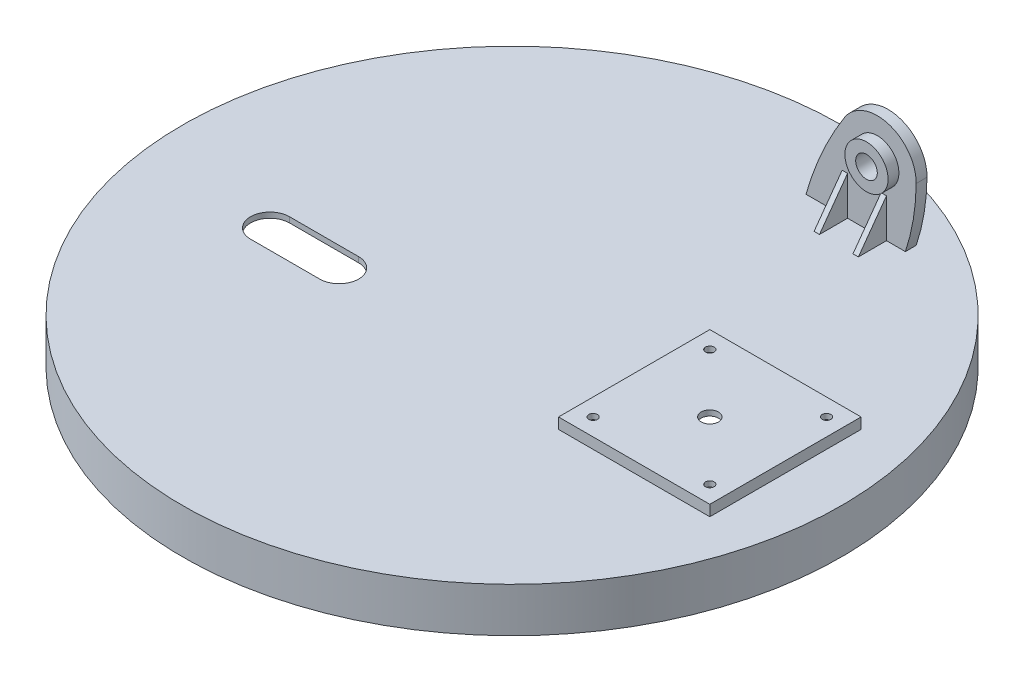
SolidWorks part; units mm, degrees
ref_plane "前视基准面" through (0, 0, 0) normal (0, 0, 1) x (1, 0, 0)
ref_plane "上视基准面" through (0, 0, 0) normal (0, 1, 0) x (1, 0, 0)
ref_plane "右视基准面" through (0, 0, 0) normal (1, 0, 0) x (0, 0, -1)
other "Configuration Table"
sketch "草图1" plane through (0, 0, 0) normal (0, 1, 0) x (1, 0, 0)
  circle A0 centre (0, 0) radius 305
  dimension "D1" = 610
extrude "凸台-拉伸1" add sketch "草图1" along normal blind 41.2
sketch "草图2" plane through (0, 41.2, 0) normal (0, 1, 0) x (1, 0, 0)
  line L0 (-182, -42) -> (-118, -42) construction
  line L1 (-182, -24) -> (-118, -24)
  line L2 (-182, -60) -> (-118, -60)
  line L3 (-200, -42) -> (-100, -42) construction
  arc A0 (-182, -24) -> (-182, -60) centre (-182, -42) ccw
  arc A1 (-118, -60) -> (-118, -24) centre (-118, -42) ccw
  point P2 (-150, -42)
  dimension "D1" = 100
  dimension "D2" = 36
  dimension "D3" = 100
  dimension "D4" = 42
sketch "草图4" plane through (0, 41.2, 0) normal (0, 1, 0) x (1, 0, 0)
  line L1 (113, 70) -> (253, 70)
  line L2 (113, 70) -> (113, -70)
  line L3 (113, -70) -> (253, -70)
  line L4 (253, 70) -> (253, -70)
  line L5 (113, 70) -> (253, -70) construction
  line L6 (113, -70) -> (253, 70) construction
  point P0 (183, 0)
  point P5 (113, 0)
  dimension "D1" = 140
  dimension "D2" = 113
extrude "凸台-拉伸2" add sketch "草图4" along normal blind 10
sketch "草图5" plane through (0, 51.2, 0) normal (0, 1, 0) x (1, 0, 0)
  line L0 (113, 70) -> (253, -70) construction
  line L1 (253, 70) -> (113, -70) construction
  line L3 (129, 54) -> (237, 54) construction
  line L4 (253, -70) -> (253, 70)
  line L5 (253, 70) -> (113, 70)
  line L6 (113, 70) -> (113, -70)
  line L7 (113, -70) -> (253, -70)
  line L8 (253, -70) -> (253, 70) construction
  line L9 (253, 70) -> (113, 70) construction
  line L10 (113, 70) -> (113, -70) construction
  line L11 (113, -70) -> (253, -70) construction
  line L12 (129, 54) -> (129, -54) construction
  line L13 (129, -54) -> (237, -54) construction
  line L14 (237, 54) -> (237, -54) construction
  line L15 (129, 54) -> (237, -54) construction
  line L16 (129, -54) -> (237, 54) construction
  circle A0 centre (183, 0) radius 8
  circle A1 centre (129, 54) radius 4
  circle A2 centre (237, 54) radius 4
  circle A3 centre (237, -54) radius 4
  circle A4 centre (129, -54) radius 4
  point P2 (373.9479, 56.6767)
  point P4 (183, 0)
  point P13 (131.7262, 0)
  dimension "D2" = 16
  dimension "D4" = 8
  dimension "D3" = 108
  dimension "D1" = 0
shell "抽壳1" thickness 5
extrude "切除-拉伸3" cut sketch "草图2" against normal through all
extrude "切除-拉伸6" cut sketch "草图5" against normal through all
sketch "草图11" plane through (0, 41.2, 0) normal (0, 1, 0) x (1, 0, 0)
  line L1 (39, 243) -> (169, 243)
  line L2 (39, 243) -> (39, 233)
  line L3 (39, 233) -> (169, 233)
  line L4 (169, 243) -> (169, 233)
  line L5 (39, 243) -> (169, 233) construction
  line L6 (39, 233) -> (169, 243) construction
  point P0 (104, 238)
  point P8 (0, 0)
  dimension "D1" = 39
  dimension "D2" = 243
  dimension "D3" = 10
  dimension "D4" = 130
extrude "凸台-拉伸3" add sketch "草图11" along normal blind 200
sketch "草图13" plane through (0, 0, -233) normal (0, 0, 1) x (1, 0, 0)
  line L0 (39, 41.2) -> (169, 41.2) construction
  line L1 (305, 41.2) -> (-305, 41.2) construction
  line L2 (39, 41.2) -> (39, 241.2)
  line L3 (39, 241.2) -> (169, 241.2)
  line L4 (169, 241.2) -> (169, 41.2)
  line L5 (113, 41.2) -> (253, 41.2) construction
  line L6 (169, 41.2) -> (131, 41.2)
  arc A0 (39, 41.2) -> (74.6468, 120.5567) centre (327.5902, -40.7493) cw
  arc A1 (74.6468, 120.5567) -> (140.998, 100.8218) centre (105, 101.2) cw
  arc A2 (140.998, 100.8218) -> (131, 41.2) centre (-53.9912, 102.8705) cw
  dimension "D2" = 300
  dimension "D3" = 36
  dimension "D4" = 195
  dimension "D1" = 105
  dimension "D5" = 92
  dimension "D6" = 60
extrude "切除-拉伸8" cut sketch "草图13" against normal through all
sketch "草图14" plane through (0, 0, -233) normal (0, 0, 1) x (1, 0, 0)
  arc A0 (140.998, 100.8218) -> (74.6468, 120.5567) centre (105, 101.2) ccw construction
  arc A1 (140.998, 100.8218) -> (74.6468, 120.5567) centre (105, 101.2) ccw
  circle A2 centre (105, 101.2) radius 20
  dimension "D1" = 40
extrude "凸台-拉伸4" add sketch "草图14" along normal blind 10 contours A2
sketch "草图16" plane through (0, 0, -223) normal (0, 0, 1) x (1, 0, 0)
  circle A0 centre (105, 101.2) radius 20 construction
  circle A1 centre (105, 101.2) radius 20
  circle A2 centre (105, 101.2) radius 10
  dimension "D1" = 20
extrude "切除-拉伸10" cut sketch "草图16" against normal through all contours A2
sketch "草图19" plane through (0, 0, -233) normal (0, 0, 1) x (1, 0, 0)
  line L0 (39, 41.2) -> (131, 41.2) construction
  line L1 (72.5, 77.2) -> (77.5, 77.2)
  line L2 (72.5, 77.2) -> (72.5, 41.2)
  line L3 (72.5, 41.2) -> (77.5, 41.2)
  line L4 (77.5, 77.2) -> (77.5, 41.2)
  line L5 (72.5, 77.2) -> (77.5, 41.2) construction
  line L6 (72.5, 41.2) -> (77.5, 77.2) construction
  line L7 (305, 41.2) -> (-305, 41.2) construction
  line L8 (108.5, 77.2) -> (113.5, 77.2)
  line L9 (108.5, 77.2) -> (108.5, 41.2)
  line L10 (108.5, 41.2) -> (113.5, 41.2)
  line L11 (113.5, 77.2) -> (113.5, 41.2)
  line L12 (108.5, 77.2) -> (113.5, 41.2) construction
  line L13 (108.5, 41.2) -> (113.5, 77.2) construction
  point P0 (75, 59.2)
  point P7 (111, 59.2)
  point P14 (75, 41.2)
  point P16 (111, 41.2)
  dimension "D1" = 5
  dimension "D2" = 75
  dimension "D3" = 36
  dimension "D4" = 36
extrude "凸台-拉伸5" add sketch "草图19" along normal blind 26
sketch "草图20" plane through (113.5, 0, 0) normal (1, 0, 0) x (0, 0, -1)
  line L0 (233, 77.2) -> (207, 41.2)
  line L1 (207, 41.2) -> (207, 77.2)
  line L2 (207, 77.2) -> (233, 77.2)
extrude "切除-拉伸11" cut sketch "草图20" against normal through all
sketch "草图21" plane through (0, 0, 0) normal (0, 0, 1) x (1, 0, 0)
  line L0 (0, 0) -> (0, -53.7646) construction
  line L1 (-85, 36.2) -> (-80, 36.2)
  line L2 (-85, 36.2) -> (-85, -15.3)
  line L3 (-85, -15.3) -> (-80, -15.3)
  line L4 (-80, 36.2) -> (-80, -15.3)
  line L5 (-85, 36.2) -> (-80, -15.3) construction
  line L6 (-85, -15.3) -> (-80, 36.2) construction
  line L7 (-75, 36.2) -> (-56, 36.2)
  line L8 (-75, 36.2) -> (-75, 31.2)
  line L9 (-75, 31.2) -> (-56, 31.2)
  line L10 (-56, 36.2) -> (-56, 31.2)
  line L11 (-75, 36.2) -> (-56, 31.2) construction
  line L12 (-75, 31.2) -> (-56, 36.2) construction
  line L13 (305, 41.2) -> (-305, 41.2) construction
  point P0 (-82.5, 10.45)
  point P5 (-65.5, 33.7)
  dimension "D1" = 170
  dimension "D2" = 150
  dimension "D3" = 5
  dimension "D4" = 19
  dimension "D5" = 51.5
  dimension "D6" = 5
  dimension "D7" = 5
revolve "旋转2" add sketch "草图21" angle 360 about L0
